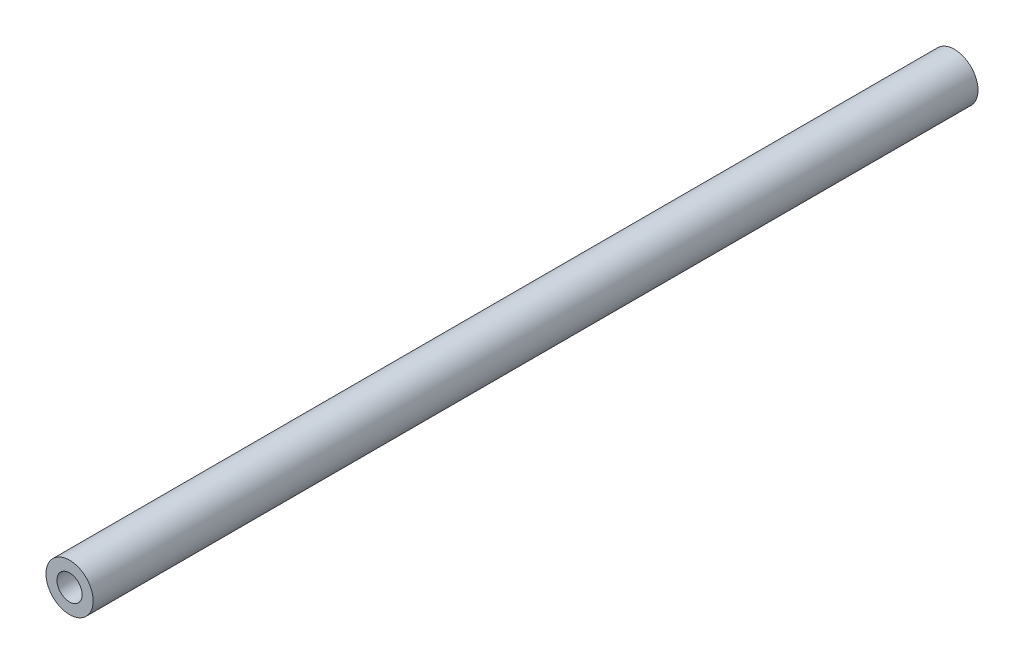
SolidWorks part; units mm, degrees
ref_plane "Piano frontale" through (0, 0, 0) normal (0, 0, 1) x (1, 0, 0)
ref_plane "Piano superiore" through (0, 0, 0) normal (0, 1, 0) x (1, 0, 0)
ref_plane "Piano destro" through (0, 0, 0) normal (1, 0, 0) x (0, 0, -1)
sketch "Schizzo1" plane through (0, 0, 0) normal (0, 0, 1) x (1, 0, 0)
  circle A0 centre (0, 0) radius 6
  dimension "D1" = 12
extrude "Estrusione-Estrusione1" add sketch "Schizzo1" along normal mid plane 225
hole_wizard "Foro per Vite M6-1" positions "Schizzo2" profile "Schizzo3" hole size "M6" standard "ISO"
sketch "Schizzo2" plane through (0, 0, 112.5) normal (0, 0, 1) x (1, 0, 0)
  point P0 (0, 0)
sketch "Schizzo3" plane through (0, 0, 112.5) normal (1, 0, 0) x (0, -1, 0)
  line L0 (0, 0) -> (0, 25)
  line L1 (0, 25) -> (3.2, 23.0772)
  line L2 (3.2, 23.0772) -> (3.2, 0)
  line L5 (3.2, 0) -> (0, 0)
  line L10 (0, 25) -> (-3.2, 23.0772) construction
  line L11 (0, -6.35) -> (0, 107.95) construction
  dimension "Hole Dia." = 6.4
  dimension "Hole Depth" = 25
  dimension "Drill Angle" = 118
mirror "Specchia1" about plane through (0, 0, 0) normal (0, 0, 1) of "Foro per Vite M6-1"
